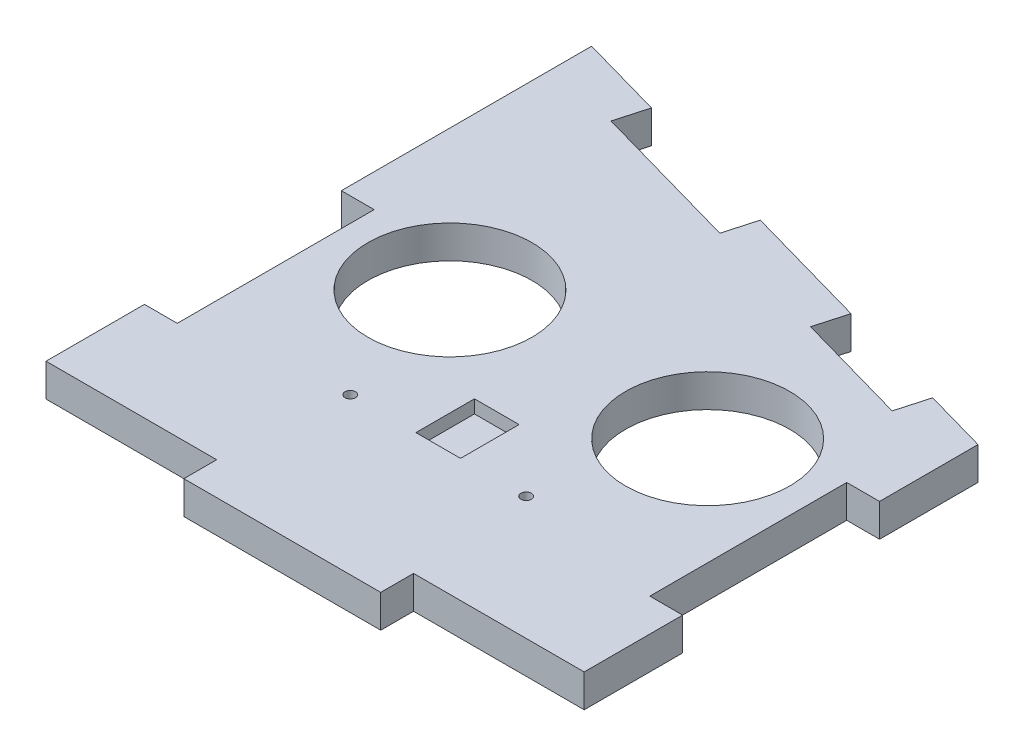
SolidWorks part; units mm, degrees
ref_plane "Front Plane" through (0, 0, 0) normal (0, 0, 1) x (1, 0, 0)
ref_plane "Top Plane" through (0, 0, 0) normal (0, 1, 0) x (1, 0, 0)
ref_plane "Right Plane" through (0, 0, 0) normal (1, 0, 0) x (0, 0, -1)
sketch "Sketch1" plane through (0, 0, 0) normal (0, 1, 0) x (1, 0, 0)
  line L0 (0, 0) -> (16.51, 0)
  line L1 (16.51, 0) -> (16.51, -3.175)
  line L2 (16.51, -3.175) -> (35.56, -3.175)
  line L3 (35.56, -3.175) -> (35.56, 0)
  line L4 (35.56, 0) -> (52.07, 0)
  line L5 (52.07, 0) -> (52.07, 9.525)
  line L6 (52.07, 9.525) -> (48.895, 9.525)
  line L7 (48.895, 9.525) -> (48.895, 28.575)
  line L8 (48.895, 28.575) -> (52.07, 28.575)
  line L9 (52.07, 28.575) -> (52.07, 38.1)
  line L10 (52.07, 38.1) -> (45.9585, 39.824)
  line L11 (0, 52.7881) -> (0, 28.575)
  line L12 (0, 28.575) -> (3.175, 28.575)
  line L13 (3.175, 28.575) -> (3.175, 9.525)
  line L14 (3.175, 9.525) -> (0, 9.525)
  line L15 (0, 9.525) -> (0, 0)
  line L16 (52.07, 38.1) -> (31.283, 38.1) construction
  line L17 (13.5699, 25.5124) -> (38.5, 25.5124) construction
  line L18 (26.035, 25.5124) -> (26.035, -3.175) construction
  line L19 (45.9585, 39.824) -> (45.0965, 36.7682)
  line L20 (45.0965, 36.7682) -> (34.0958, 39.8713)
  line L21 (34.0958, 39.8713) -> (34.9578, 42.9271)
  line L22 (34.9578, 42.9271) -> (22.7348, 46.375)
  line L23 (22.7348, 46.375) -> (21.8728, 43.3193)
  line L24 (21.8728, 43.3193) -> (7.2052, 47.4568)
  line L25 (7.2052, 47.4568) -> (8.0672, 50.5125)
  line L26 (8.0672, 50.5125) -> (0, 52.7881)
  line L27 (3.175, 28.575) -> (3.175, 51.8925) construction
  line L28 (3.175, 9.525) -> (3.175, 0) construction
  line L29 (48.895, 28.575) -> (48.895, 38.9956) construction
  line L30 (48.895, 9.525) -> (48.895, 0) construction
  circle A0 centre (13.5699, 25.5124) radius 7.9375
  circle A1 centre (38.5, 25.5124) radius 7.9375
  dimension "D1" = 15.875
  dimension "D2" = 45.72
  dimension "D3" = 3.175
  dimension "D4" = 38.1
  dimension "D5" = 3.175
  dimension "D6" = 19.05
  dimension "D7" = 19.05
  dimension "D8" = 24.9301
  dimension "D9" = 15.24
  dimension "D10" = 11.43
  dimension "D11" = 8.382
  dimension "D12" = 12.7
  dimension "D13" = 6.35
  dimension "D14" = 54.102
  dimension "D15" = 51.8925
  dimension "D16" = 38.9956
  dimension "D17" = 9.525
  dimension "D18" = 52.7881
extrude "Boss-Extrude1" add sketch "Sketch1" along normal blind 3.175
sketch "Sketch2" plane through (0, 3.175, 0) normal (0, 1, 0) x (1, 0, 0)
  line L0 (38.5, 17.5749) -> (20.6827, 17.5749) construction
  line L1 (23.876, 17.5749) -> (28.194, 17.5749)
  line L2 (23.876, 17.5749) -> (23.876, 11.9107)
  line L3 (23.876, 11.9107) -> (28.194, 11.9107)
  line L4 (28.194, 17.5749) -> (28.194, 11.9107)
  line L5 (26.035, -3.175) -> (26.035, 11.9107) construction
  line L6 (16.51, -3.175) -> (35.56, -3.175) construction
  circle A0 centre (38.5, 25.5124) radius 7.9375 construction
  dimension "D1" = 5.6642
  dimension "D2" = 4.318
extrude "Cut-Extrude1" cut sketch "Sketch2" against normal blind 1.27
sketch "Sketch3" plane through (0, 3.175, 0) normal (0, 1, 0) x (1, 0, 0)
  line L0 (23.876, 11.9107) -> (17.526, 11.9107) construction
  line L1 (28.194, 11.9107) -> (34.544, 11.9107) construction
  circle A0 centre (17.526, 11.9107) radius 0.508
  circle A1 centre (34.544, 11.9107) radius 0.508
  dimension "D1" = 1.016
  dimension "D2" = 6.35
extrude "Cut-Extrude2" cut sketch "Sketch3" against normal through all
